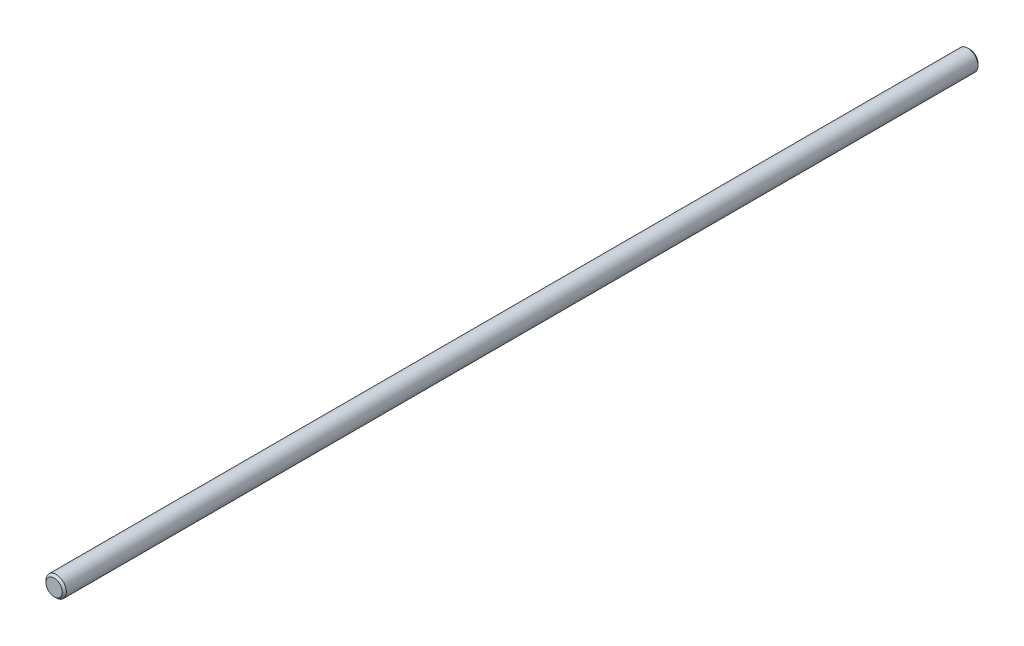
SolidWorks part; units mm, degrees
material "Alloy Steel (SS)"
ref_plane "Front Plane" through (0, 0, 0) normal (0, 0, 1) x (1, 0, 0)
ref_plane "Top Plane" through (0, 0, 0) normal (0, 1, 0) x (1, 0, 0)
ref_plane "Right Plane" through (0, 0, 0) normal (1, 0, 0) x (0, 0, -1)
sketch "Sketch1" plane through (0, 0, 0) normal (0, 0, 1) x (1, 0, 0)
  circle A0 centre (0, 0) radius 1
  dimension "D1" = 2
extrude "Boss-Extrude1" add sketch "Sketch1" along normal blind 90
chamfer "Chamfer1" distance 0.2 angle 45 2 edges at (1, 0, 90) (1, 0, 0)
